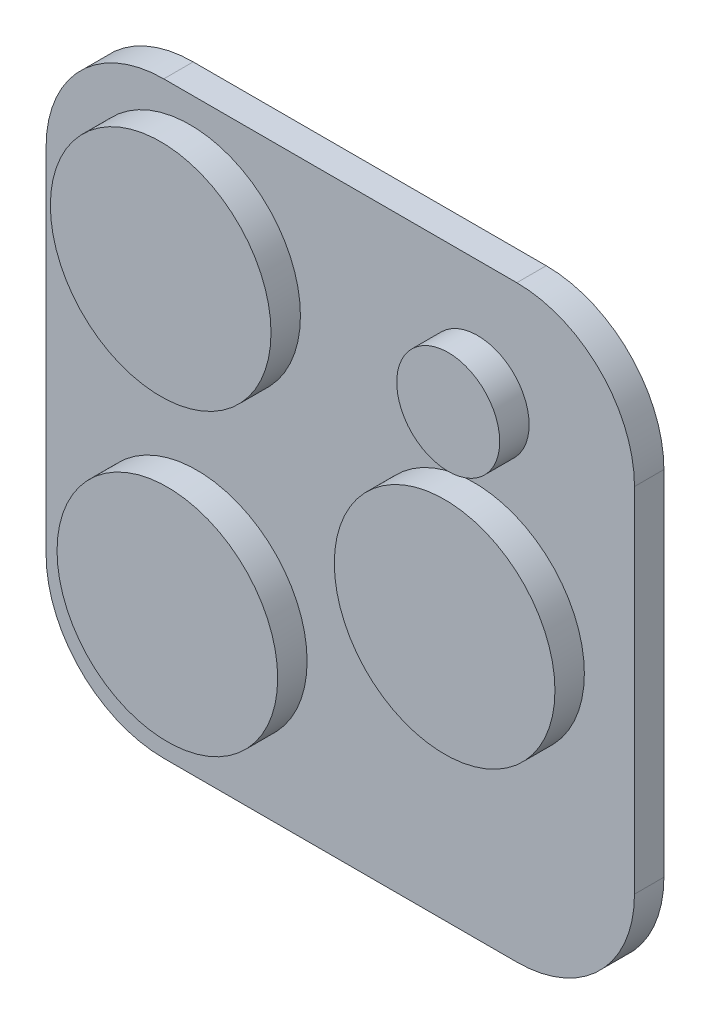
SolidWorks part; units mm, degrees
ref_plane "前视基准面" through (0, 0, 0) normal (0, 0, 1) x (1, 0, 0)
ref_plane "上视基准面" through (0, 0, 0) normal (0, 1, 0) x (1, 0, 0)
ref_plane "右视基准面" through (0, 0, 0) normal (1, 0, 0) x (0, 0, -1)
other "Configuration Table"
sketch "草图1" plane through (0, 0, 0) normal (0, 0, 1) x (1, 0, 0)
  line L1 (-34.263, 15.841) -> (-10.263, 15.841)
  line L2 (-42.263, 7.841) -> (-42.263, -16.159)
  line L3 (-34.263, -24.159) -> (-10.263, -24.159)
  line L4 (-2.263, 7.841) -> (-2.263, -16.159)
  arc A0 (-10.263, -24.159) -> (-2.263, -16.159) centre (-10.263, -16.159) ccw
  arc A1 (-34.263, -24.159) -> (-42.263, -16.159) centre (-34.263, -16.159) cw
  arc A2 (-10.263, 15.841) -> (-2.263, 7.841) centre (-10.263, 7.841) cw
  arc A3 (-42.263, 7.841) -> (-34.263, 15.841) centre (-34.263, 7.841) cw
  point P8 (-42.263, -24.159)
  point P11 (-2.263, 15.841)
  point P14 (-42.263, 15.841)
  dimension "D3" = 8
  dimension "D1" = 40
  dimension "D2" = 40
extrude "凸台-拉伸1" add sketch "草图1" along normal blind 2
sketch "草图2" plane through (0, 0, 2) normal (0, 0, 1) x (1, 0, 0)
  circle A1 centre (-32.4728, 6.5395) radius 7.5
  circle A2 centre (-32.0191, -13.566) radius 7.5
  circle A3 centre (-13.1701, -4.8746) radius 7.5
  circle A4 centre (-12.9258, 7.9008) radius 3.5
  point P2 (-12.8909, 8.9829)
  point P7 (0, 0)
  point P8 (0, 0)
  point P11 (0, 0)
  point P12 (-12.9258, 7.9008)
extrude "凸台-拉伸2" add sketch "草图2" along normal blind 2
